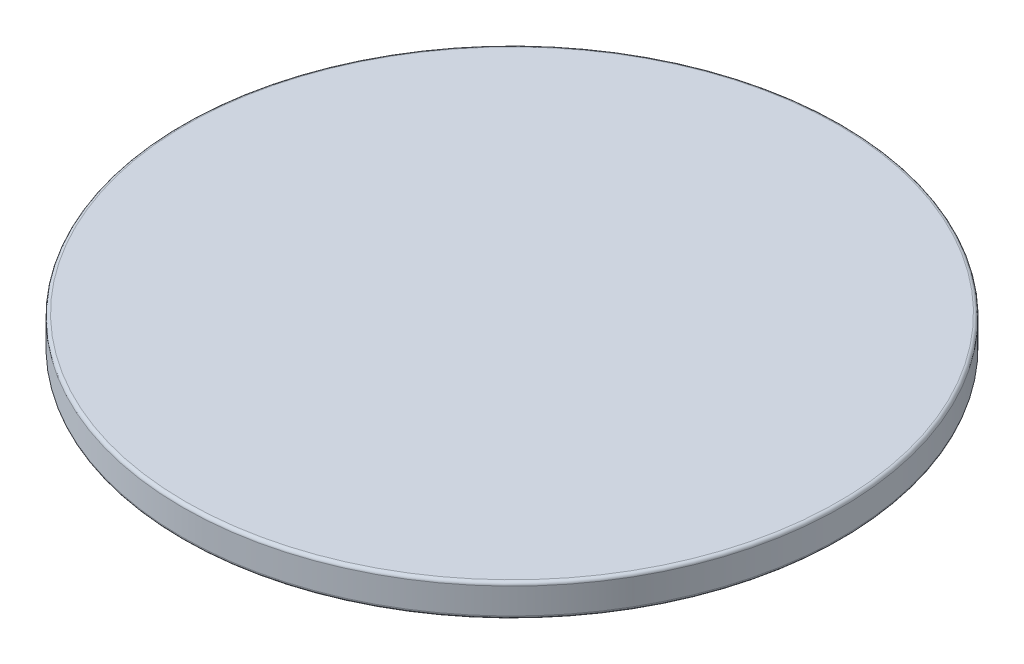
SolidWorks part; units mm, degrees
ref_plane "Front" through (0, 0, 0) normal (0, 0, 1) x (1, 0, 0)
ref_plane "Top" through (0, 0, 0) normal (0, 1, 0) x (1, 0, 0)
ref_plane "Right" through (0, 0, 0) normal (1, 0, 0) x (0, 0, -1)
sketch "Sketch2" plane through (0, 0, 0) normal (0, 1, 0) x (1, 0, 0)
  circle A0 centre (0, 0) radius 64.77
  dimension "D1" = 129.54
extrude "Boss-Extrude1" add sketch "Sketch2" along normal blind 6.35
fillet "Fillet1" radius 0.635 2 edges at (0, 0, 64.77) (0, 6.35, 64.77)
